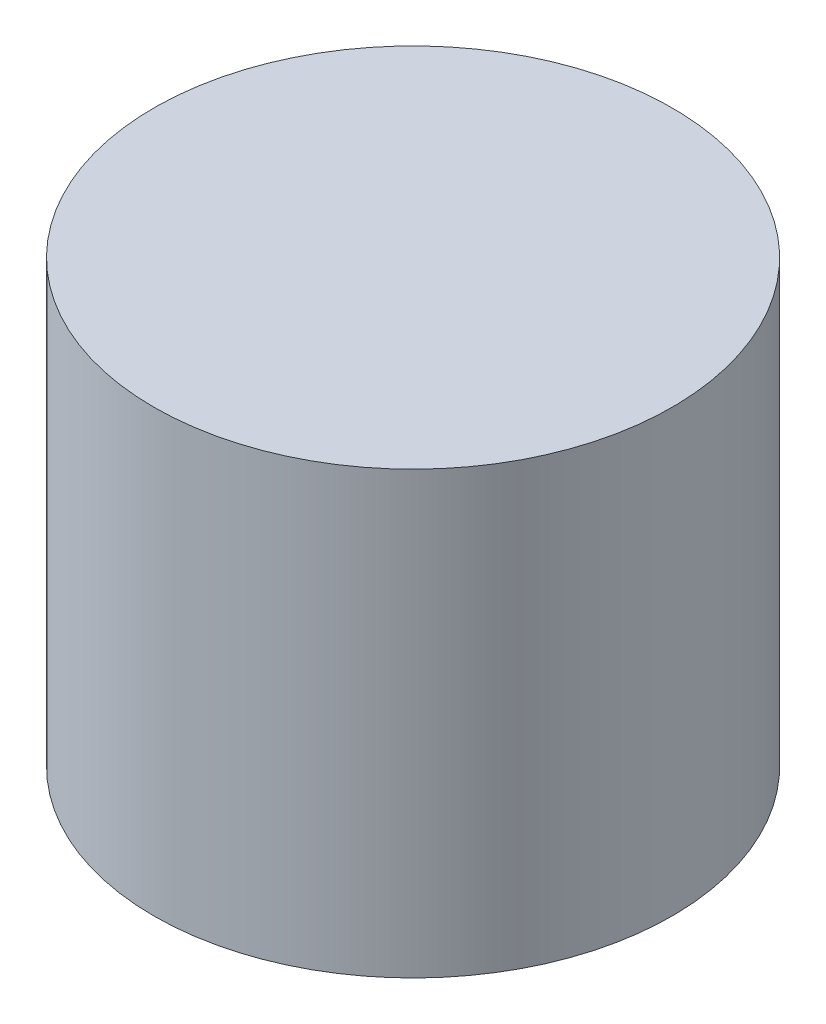
SolidWorks part; units mm, degrees
ref_plane "Front Plane" through (0, 0, 0) normal (0, 0, 1) x (1, 0, 0)
ref_plane "Top Plane" through (0, 0, 0) normal (0, 1, 0) x (1, 0, 0)
ref_plane "Right Plane" through (0, 0, 0) normal (1, 0, 0) x (0, 0, -1)
sketch "Эскиз1" plane through (0, 0, 0) normal (0, 1, 0) x (1, 0, 0)
  circle A0 centre (0, 0) radius 10
extrude "Бобышка-Вытянуть1" add sketch "Эскиз1" along normal blind 17
